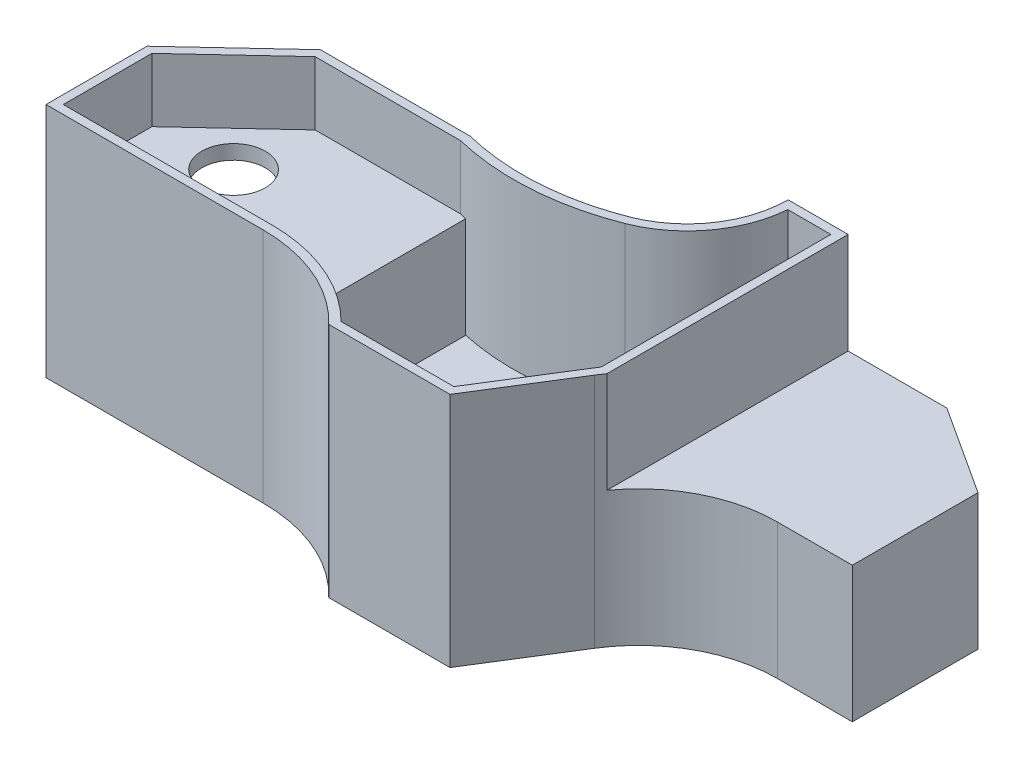
SolidWorks part; units mm, degrees
material "AISI 1020"
ref_plane "Front Plane" through (0, 0, 0) normal (0, 0, 1) x (1, 0, 0)
ref_plane "Top Plane" through (0, 0, 0) normal (0, 1, 0) x (1, 0, 0)
ref_plane "Right Plane" through (0, 0, 0) normal (1, 0, 0) x (0, 0, -1)
sketch "Sketch1" plane through (0, 0, 0) normal (0, 1, 0) x (1, 0, 0)
  line L0 (157.2027, 100) -> (212.2027, 100)
  line L1 (212.2027, 100) -> (243, 80)
  line L2 (243, 80) -> (243, 36.4402)
  line L3 (243, 36.4402) -> (217, 36.4402)
  line L4 (176.2937, 13.8764) -> (157, -17)
  line L5 (157, -17) -> (115, -17)
  line L6 (75.2382, 0) -> (0, 0)
  line L7 (0, 0) -> (0, 35)
  line L8 (0, 35) -> (31.0987, 64)
  line L9 (83, 64) -> (31.0987, 64)
  line L10 (212.2027, 100) -> (32.6444, 100) construction
  line L11 (243, 80) -> (243, -2.5299) construction
  line L12 (157, -17) -> (115, -17) construction
  line L13 (35.4764, -17) -> (30.2288, -17) construction
  line L14 (0, 35) -> (0, 90.8289) construction
  circle A0 centre (135, 43) radius 16.5
  arc A2 (243, 28.7887) -> (176.2937, 13.8764) centre (217, -11.5598) ccw
  arc A3 (115, -17) -> (75.2382, 0) centre (75.2382, -55) ccw
  arc A4 (134.9892, 67.4192) -> (157.2027, 100) centre (122.2027, 100) ccw
  arc A6 (83, 64) -> (134.9892, 67.4192) centre (103.6263, 147.3338) ccw
  dimension "D1" = 33
  dimension "D2" = 96
  dimension "D3" = 17
  dimension "D6" = 110
  dimension "D8" = 70
  dimension "D14" = 42
  dimension "D17" = 102
  dimension "D18" = 81
  dimension "D20" = 83
  dimension "D4" = 85.8485
  dimension "D21" = 47
  dimension "D5" = 35
  dimension "D7" = 117
  dimension "D9" = 55
  dimension "D10" = 57
  dimension "D11" = 97
  dimension "D12" = 60
  dimension "D13" = 58
  dimension "D15" = 115
  dimension "D16" = 20
  dimension "D19" = 128
extrude "Boss-Extrude1" add sketch "Sketch1" along normal blind 82 contours A6 L9 L8 L7 L6 A3 L5 L4 A2 L3 L2 L1 L0 A4 A0
sketch "Sketch2" plane through (0, 82, 0) normal (0, 1, 0) x (1, 0, 0)
  circle A0 centre (30, 35) radius 11
  dimension "D1" = 22
  dimension "D2" = 35
  dimension "D3" = 30
extrude "Cut-Extrude1" cut sketch "Sketch2" against normal through all contours A0
sketch "Sketch5" plane through (0, 0, -100) normal (0, 0, -1) x (-1, 0, 0)
  line L0 (-157.2027, 82) -> (-212.2027, 82) construction
  line L1 (-178, 82) -> (-243, 82)
  line L2 (-178, 82) -> (-178, 47)
  line L3 (-178, 47) -> (-243, 47)
  line L4 (-243, 82) -> (-243, 47)
  line L5 (-243, 82) -> (-243, 0) construction
  dimension "D1" = 65
extrude "Cut-Extrude2" cut sketch "Sketch5" against normal through all
ref_plane "Plane1" through (0, 15, 0) normal (0, -1, 0) x (-1, 0, 0)
sketch "Sketch6" plane through (0, 15, 0) normal (0, -1, 0) x (-1, 0, 0)
  line L0 (0, 0) -> (0, 35) construction
  line L1 (-83, 64) -> (-31.0987, 64) construction
  line L2 (0, 12) -> (0, 35)
  line L3 (-74.6896, 64) -> (-31.0987, 64)
  line L4 (0, 35) -> (-31.0987, 64) construction
  line L5 (0, 35) -> (-31.0987, 64)
  arc A1 (-74.6896, 64) -> (0, 12) centre (-15, 70.0948) ccw
  point P6 (0, 12)
  point P8 (0, 0)
  dimension "D1" = 120
  dimension "D2" = 100
  dimension "D3" = 12
extrude "Cut-Extrude3" cut sketch "Sketch6" against normal blind 40
sketch "Sketch9" plane through (0, 82, 0) normal (0, 1, 0) x (1, 0, 0)
  line L0 (175, 17.3712) -> (175, 97)
  line L1 (175, 97) -> (160.0841, 97)
  line L2 (82.6374, 61) -> (32.2804, 61)
  line L3 (32.2804, 61) -> (3, 33.6956)
  line L4 (3, 33.6956) -> (3, 3)
  line L5 (3, 3) -> (75.2382, 3)
  line L6 (116.2626, -14) -> (155.3371, -14)
  line L7 (155.3371, -14) -> (173.7495, 15.4661)
  line L8 (178, 16.4224) -> (178, 100)
  line L9 (178, 100) -> (157.2027, 100)
  line L10 (83, 64) -> (31.0987, 64)
  line L11 (31.0987, 64) -> (0, 35)
  line L12 (0, 35) -> (0, 0)
  line L13 (0, 0) -> (75.2382, 0)
  line L14 (115, -17) -> (157, -17)
  line L15 (157, -17) -> (176.2937, 13.8764)
  line L16 (178, 16.4224) -> (178, 100)
  line L17 (178, 100) -> (157.2027, 100)
  line L18 (83, 64) -> (31.0987, 64)
  line L19 (31.0987, 64) -> (0, 35)
  line L20 (0, 35) -> (0, 0)
  line L21 (0, 0) -> (75.2382, 0)
  line L22 (115, -17) -> (157, -17)
  line L23 (157, -17) -> (176.2937, 13.8764)
  line L24 (85, 60.4596) -> (85, 2.1726)
  arc A0 (136.0852, 64.6266) -> (160.0841, 97) centre (122.2027, 100) ccw
  arc A1 (82.6374, 61) -> (136.0852, 64.6266) centre (103.6263, 147.3338) ccw
  arc A2 (116.2626, -14) -> (75.2382, 3) centre (75.2382, -55) ccw
  arc A3 (175, 17.3712) -> (173.7495, 15.4661) centre (217, -11.5598) ccw
  arc A4 (134.9892, 67.4192) -> (157.2027, 100) centre (122.2027, 100) ccw
  arc A5 (83, 64) -> (134.9892, 67.4192) centre (103.6263, 147.3338) ccw
  arc A6 (115, -17) -> (75.2382, 0) centre (75.2382, -55) ccw
  arc A7 (178, 16.4224) -> (176.2937, 13.8764) centre (217, -11.5598) ccw
  arc A8 (134.9892, 67.4192) -> (157.2027, 100) centre (122.2027, 100) ccw
  arc A9 (83, 64) -> (134.9892, 67.4192) centre (103.6263, 147.3338) ccw
  arc A10 (115, -17) -> (75.2382, 0) centre (75.2382, -55) ccw
  arc A11 (178, 16.4224) -> (176.2937, 13.8764) centre (217, -11.5598) ccw
  circle M37 centre (30, 35) radius 11
  dimension "D3" = 30
  dimension "D1" = 0
  dimension "D2" = 3
extrude "Cut-Extrude4" cut sketch "Sketch9" against normal offset from surface (22 mm away) 5 contours A2 L24 A1 L2 L3 L4 L5 M37 up to face at (29.4315, 55, -39.4634)
sketch "Sketch10" plane through (0, 82, 0) normal (0, 1, 0) x (1, 0, 0)
  line L0 (32.2804, 61) -> (3, 33.6956)
  line L1 (3, 33.6956) -> (3, 3)
  line L2 (3, 3) -> (75.2382, 3)
  line L3 (116.2626, -14) -> (155.3371, -14)
  line L4 (155.3371, -14) -> (173.7495, 15.4661)
  line L5 (175, 17.3712) -> (175, 97)
  line L6 (175, 97) -> (160.0841, 97)
  line L7 (82.6374, 61) -> (32.2804, 61)
  line L8 (178, 16.4224) -> (178, 100)
  line L9 (178, 100) -> (157.2027, 100)
  line L10 (83, 64) -> (31.0987, 64)
  line L11 (31.0987, 64) -> (0, 35)
  line L12 (0, 35) -> (0, 0)
  line L13 (0, 0) -> (75.2382, 0)
  line L14 (115, -17) -> (157, -17)
  line L15 (157, -17) -> (176.2937, 13.8764)
  line L16 (178, 16.4224) -> (178, 100)
  line L17 (178, 100) -> (157.2027, 100)
  line L18 (83, 64) -> (31.0987, 64)
  line L19 (31.0987, 64) -> (0, 35)
  line L20 (0, 35) -> (0, 0)
  line L21 (0, 0) -> (75.2382, 0)
  line L22 (115, -17) -> (157, -17)
  line L23 (157, -17) -> (176.2937, 13.8764)
  line L24 (85, 60.4596) -> (85, 2.1726)
  line L25 (85, 60.4596) -> (85, 63.5303)
  line L26 (85, 2.1726) -> (85, -0.8732)
  arc A0 (116.2626, -14) -> (75.2382, 3) centre (75.2382, -55) ccw
  arc A1 (175, 17.3712) -> (173.7495, 15.4661) centre (217, -11.5598) ccw
  arc A2 (136.0852, 64.6266) -> (160.0841, 97) centre (122.2027, 100) ccw
  arc A3 (82.6374, 61) -> (136.0852, 64.6266) centre (103.6263, 147.3338) ccw
  arc A4 (134.9892, 67.4192) -> (157.2027, 100) centre (122.2027, 100) ccw
  arc A5 (83, 64) -> (134.9892, 67.4192) centre (103.6263, 147.3338) ccw
  arc A6 (115, -17) -> (75.2382, 0) centre (75.2382, -55) ccw
  arc A7 (178, 16.4224) -> (176.2937, 13.8764) centre (217, -11.5598) ccw
  arc A8 (134.9892, 67.4192) -> (157.2027, 100) centre (122.2027, 100) ccw
  arc A9 (83, 64) -> (134.9892, 67.4192) centre (103.6263, 147.3338) ccw
  arc A10 (115, -17) -> (75.2382, 0) centre (75.2382, -55) ccw
  arc A11 (178, 16.4224) -> (176.2937, 13.8764) centre (217, -11.5598) ccw
  circle M14 centre (135, 43) radius 16.5
  line M28 (85, 60.4596) -> (85, 2.1726)
  dimension "D1" = 0
  dimension "D2" = 3
extrude "Cut-Extrude5" cut sketch "Sketch10" against normal blind 57 contours A3 A0 L3 L4 A1 L5 L6 A2 M28 M14
